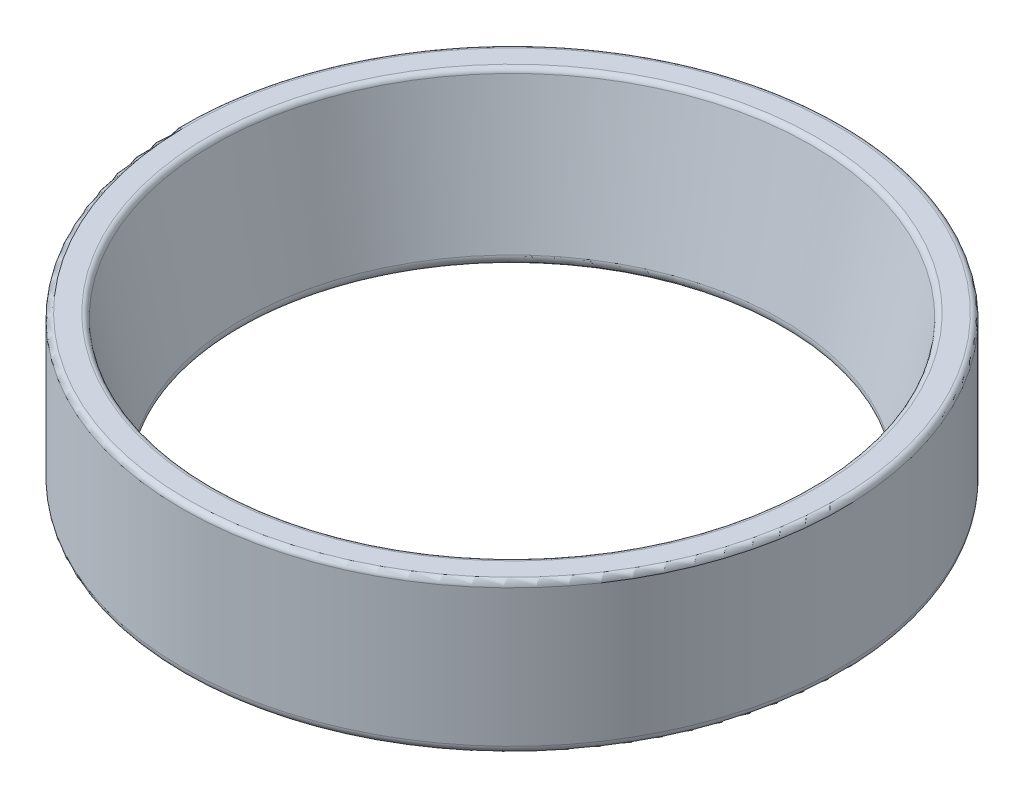
SolidWorks part; units mm, degrees
ref_plane "Front Plane" through (0, 0, 0) normal (0, 0, 1) x (1, 0, 0)
ref_plane "Top Plane" through (0, 0, 0) normal (0, 1, 0) x (1, 0, 0)
ref_plane "Right Plane" through (0, 0, 0) normal (1, 0, 0) x (0, 0, -1)
sketch "Sketch1" plane through (0, 0, 0) normal (0, 0, 1) x (1, 0, 0)
  line L0 (0, 17.6909) -> (0, 0) construction
  line L1 (0, 0) -> (-30.5, 0) construction
  line L2 (-30.5, 13.5) -> (-30.5, 0.8)
  line L3 (-29.7, 0) -> (-25.7396, 0)
  line L4 (-24.9573, 0.9676) -> (-27.6653, 13.6048)
  line L5 (-28.1542, 14) -> (-30, 14)
  arc A0 (-29.7, 0) -> (-30.5, 0.8) centre (-29.7, 0.8) cw
  arc A1 (-25.7396, 0) -> (-24.9573, 0.9676) centre (-25.7396, 0.8) ccw
  arc A2 (-27.6653, 13.6048) -> (-28.1542, 14) centre (-28.1542, 13.5) ccw
  arc A3 (-30.5, 13.5) -> (-30, 14) centre (-30, 13.5) cw
  point P12 (-24.75, 0)
  point P15 (-27.75, 14)
  point P18 (-30.5, 14)
  dimension "D5" = 0.8
  dimension "D6" = 0.5
  dimension "D1" = 30.5
  dimension "D2" = 14
  dimension "D3" = 5.75
  dimension "D4" = 2.75
revolve "Revolve1" add sketch "Sketch1" angle 360 about L0
